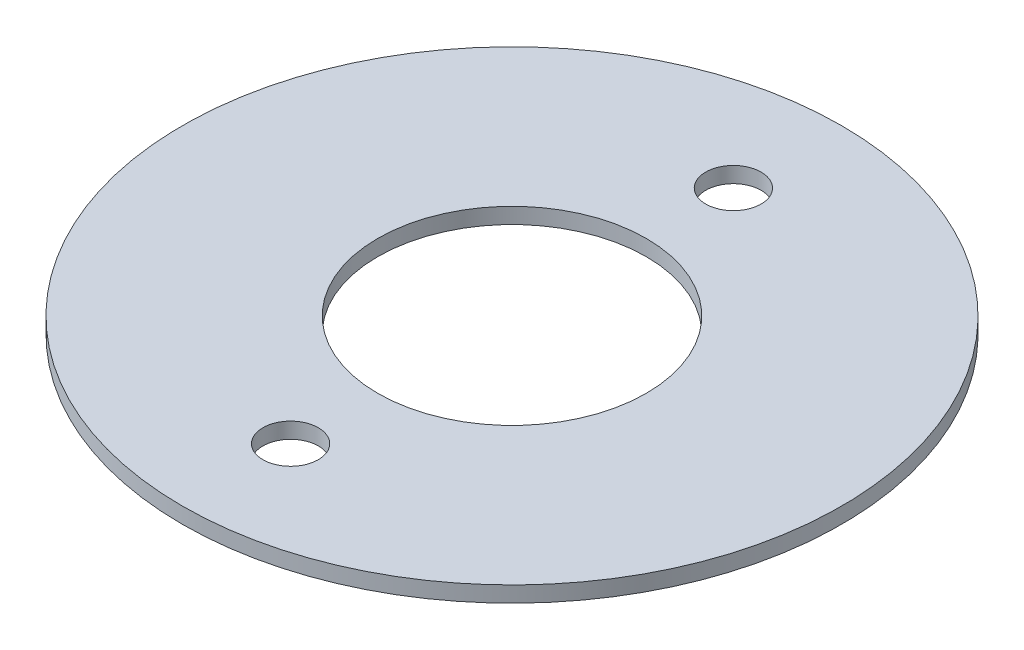
SolidWorks part; units mm, degrees
material "LE Phenolic"
ref_plane "Front Plane" through (0, 0, 0) normal (0, 0, 1) x (1, 0, 0)
ref_plane "Top Plane" through (0, 0, 0) normal (0, 1, 0) x (1, 0, 0)
ref_plane "Right Plane" through (0, 0, 0) normal (1, 0, 0) x (0, 0, -1)
sketch "Sketch1" plane through (0, 0, 0) normal (0, 1, 0) x (1, 0, 0)
  circle A0 centre (0, 0) radius 66.167
  dimension "D1" = 132.334
extrude "Boss-Extrude1" add sketch "Sketch1" along normal blind 3.175
sketch "Sketch2" plane through (0, 0, 0) normal (0, -1, 0) x (1, 0, 0)
  circle A0 centre (0, -44.45) radius 5.5626 construction
  circle A1 centre (0, 0) radius 26.9494 construction
  circle A2 centre (0, 44.45) radius 5.5626 construction
  circle A3 centre (0, -44.45) radius 5.5626
  circle A4 centre (0, 0) radius 26.9494
  circle A5 centre (0, 44.45) radius 5.5626
extrude "Cut-Extrude1" cut sketch "Sketch2" against normal through all
